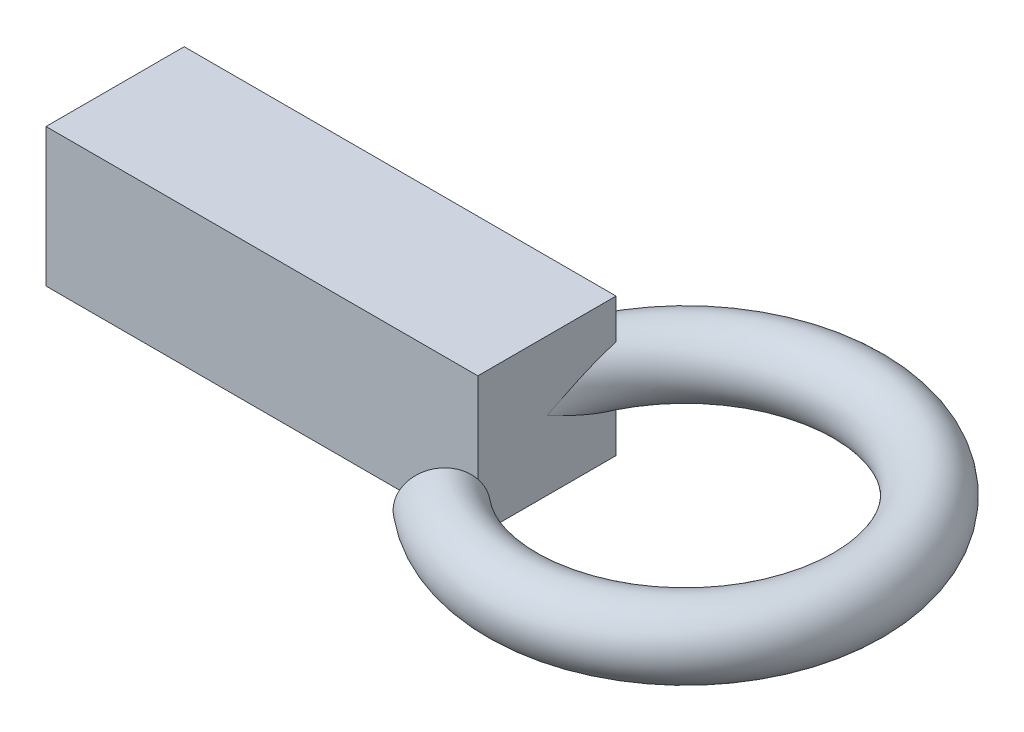
SolidWorks part; units mm, degrees
ref_plane "Front Plane" through (0, 0, 0) normal (0, 0, 1) x (1, 0, 0)
ref_plane "Top Plane" through (0, 0, 0) normal (0, 1, 0) x (1, 0, 0)
ref_plane "Right Plane" through (0, 0, 0) normal (1, 0, 0) x (0, 0, -1)
sketch "Sketch1" plane through (0, 0, 0) normal (0, 1, 0) x (1, 0, 0)
  arc A3 (7.1442, -15.3209) -> (0, 0) centre (20, 0) ccw
sketch "Sketch2" plane through (0, 0, 0) normal (0, 0, 1) x (1, 0, 0)
  circle A0 centre (0, 0) radius 4
sweep "Sweep1" add profiles "Sketch2" path "Sketch1"
sketch "Sketch3" plane through (0, 0, 0) normal (0, 1, 0) x (1, 0, 0)
  line L2 (4, -8) -> (-46, -8)
  line L3 (4, -8) -> (4, 8)
  line L4 (4, 8) -> (-46, 8)
  line L5 (-46, -8) -> (-46, 8)
extrude "Boss-Extrude1" add sketch "Sketch3" along normal mid plane 16
hole_wizard "M8 Tapped Hole1" positions "Sketch4" profile "Sketch5" tap size "M8" standard "ISO"
sketch "Sketch4" plane through (-46, 0, 0) normal (-1, 0, 0) x (0, 0, 1)
  point P0 (0, 0)
sketch "Sketch5" plane through (-46, 0, 0) normal (0, 1, 0) x (0, 0, 1)
  line L0 (0, 0) -> (0, 32.0429)
  line L1 (0, 32.0429) -> (3.4, 30)
  line L2 (3.4, 30) -> (3.4, 0)
  line L5 (3.4, 0) -> (0, 0)
  line L10 (0, 32.0429) -> (-3.4, 30) construction
  line L11 (0, -6.35) -> (0, 107.95) construction
  dimension "Tap Drill Dia." = 6.8
  dimension "Tap Drill Depth" = 30
  dimension "Drill Angle" = 118
cosmetic thread "Hole Thread1" parameters "D1"=30, "D2"=8
sketch "Sketch6" plane through (0, 0, 0) normal (0, 1, 0) x (1, 0, 0)
  line L0 (36, 0) -> (32, 0)
  arc A0 (9.7154, -12.2567) -> (4, 0.0001) centre (20, 0) ccw construction
